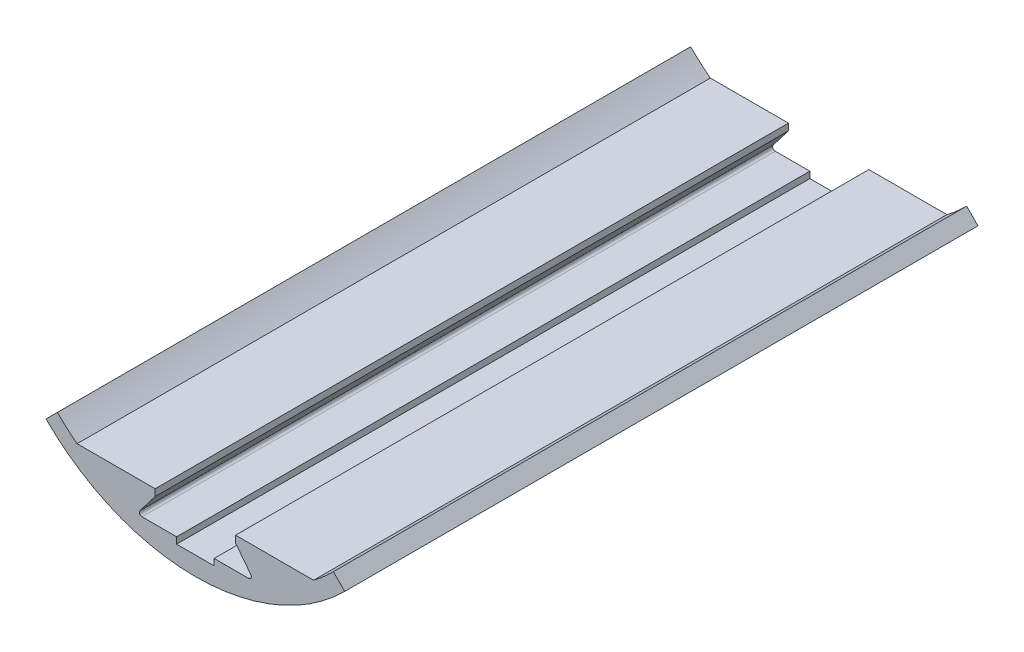
SolidWorks part; units mm, degrees
ref_plane "Front Plane" through (0, 0, 0) normal (0, 0, 1) x (1, 0, 0)
ref_plane "Top Plane" through (0, 0, 0) normal (0, 1, 0) x (1, 0, 0)
ref_plane "Right Plane" through (0, 0, 0) normal (1, 0, 0) x (0, 0, -1)
sketch "Sketch1" plane through (0, 0, 0) normal (0, 0, 1) x (1, 0, 0)
  line L0 (32.6881, -32.6881) -> (35.3822, -35.3822)
  line L1 (-32.6881, -32.6881) -> (-35.3822, -35.3822)
  line L2 (0, 0) -> (0, -50.038) construction
  arc A0 (-35.3822, -35.3822) -> (35.3822, -35.3822) centre (0, 0) ccw
  arc A1 (-32.6881, -32.6881) -> (32.6881, -32.6881) centre (0, 0) ccw
  dimension "D1" = 100.076
  dimension "D2" = 3.81
  dimension "D3" = 90
extrude "Boss-Extrude1" add sketch "Sketch1" against normal blind 150 contours A0 L0 A1 L1
sketch "Sketch2" plane through (0, 0, 0) normal (0, 0, 1) x (1, 0, 0)
  line L0 (13.828, -33.6) -> (-13.828, -33.6) construction
  line L1 (-28.0112, -36.775) -> (-9.525, -36.775)
  line L2 (-9.525, -36.775) -> (-9.525, -38.3705)
  line L3 (-9.525, -38.3705) -> (-13.1264, -43.0639)
  line L4 (-12.6226, -44.0855) -> (12.6226, -44.0855)
  line L5 (13.1264, -43.0639) -> (9.525, -38.3705)
  line L6 (9.525, -38.3705) -> (9.525, -36.775)
  line L7 (9.525, -36.775) -> (28.0112, -36.775)
  line L8 (0, -46.228) -> (0, -35.5149) construction
  line L9 (-4.445, -44.0855) -> (-4.445, -45.6095)
  line L10 (-4.445, -45.6095) -> (4.445, -45.6095)
  line L11 (4.445, -45.6095) -> (4.445, -44.0855)
  arc A0 (-32.6881, -32.6881) -> (32.6881, -32.6881) centre (0, 0) ccw construction
  arc A1 (-28.0112, -36.775) -> (28.0112, -36.775) centre (0, 0) ccw
  arc A2 (-13.1264, -43.0639) -> (-12.6226, -44.0855) centre (-12.6226, -43.4505) ccw
  arc A3 (12.6226, -44.0855) -> (13.1264, -43.0639) centre (12.6226, -43.4505) ccw
  point P18 (-13.9103, -44.0855)
  point P21 (13.9103, -44.0855)
  arc M13 (32.6881, -32.6881) -> (-32.6881, -32.6881) centre (0, 0) cw
  dimension "D4" = 0.635
  dimension "D1" = 19.05
  dimension "D2" = 75
  dimension "D3" = 5.715
  dimension "D5" = 3.175
  dimension "D6" = 1.524
  dimension "D7" = 8.89
extrude "Boss-Extrude2" add sketch "Sketch2" against normal up to surface (150 mm away) contours A1 L8 L10 L9 L4 A2 L3 L2 L1 | L8 L7 L6 L5 A3 L4 L11 L10 M13 up to face at (0, -41.0841, -150)
